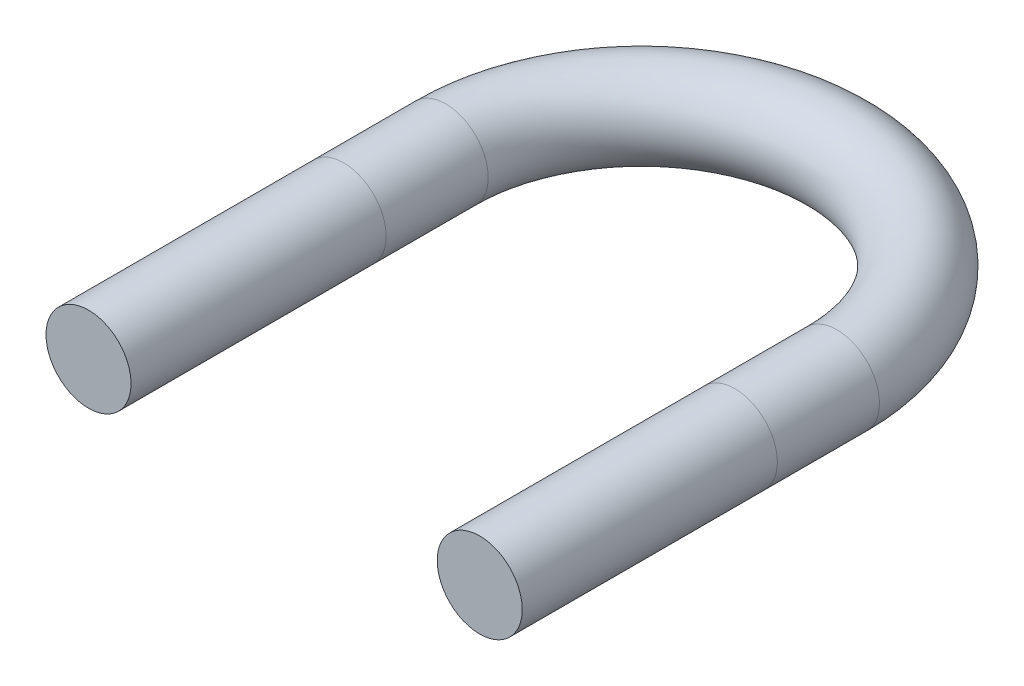
SolidWorks part; units mm, degrees
material "Stainless Steel (ferritic)"
ref_plane "Front Plane" through (0, 0, 0) normal (0, 0, 1) x (1, 0, 0)
ref_plane "Top Plane" through (0, 0, 0) normal (0, 1, 0) x (1, 0, 0)
ref_plane "Right Plane" through (0, 0, 0) normal (1, 0, 0) x (0, 0, -1)
sketch "Sketch1" plane through (0, 0, 0) normal (0, 1, 0) x (1, 0, 0)
  line L0 (-23, 0) -> (-23, -42)
  line L1 (0, 0) -> (0, -42) construction
  line L2 (23, 0) -> (23, -42)
  circle A0 centre (0, 0) radius 23 construction
  arc A1 (-23, 0) -> (23, 0) centre (0, 0) cw
  dimension "D1" = 46
  dimension "D2" = 42
sweep "Sweep1" add path "Sketch1" circular profile diameter 10 parameters "D3"=10
sketch "Sketch9" plane through (0, 0, 0) normal (0, 1, 0) x (1, 0, 0)
  line L0 (23, 0) -> (23, -42) construction
  line L1 (23, 0) -> (23, -42) construction
  line L2 (42.7669, -12) -> (-41.0168, -12)
  dimension "D1" = 30
split line "Split Line1"
cosmetic thread "Cosmetic Thread1" parameters "D2"=8.344
cosmetic thread "Cosmetic Thread2" parameters "D2"=8.344
equation "\"D1@Sketch1\"=(18+5)*2"
equation "\"D2@Sketch1\"=42"
